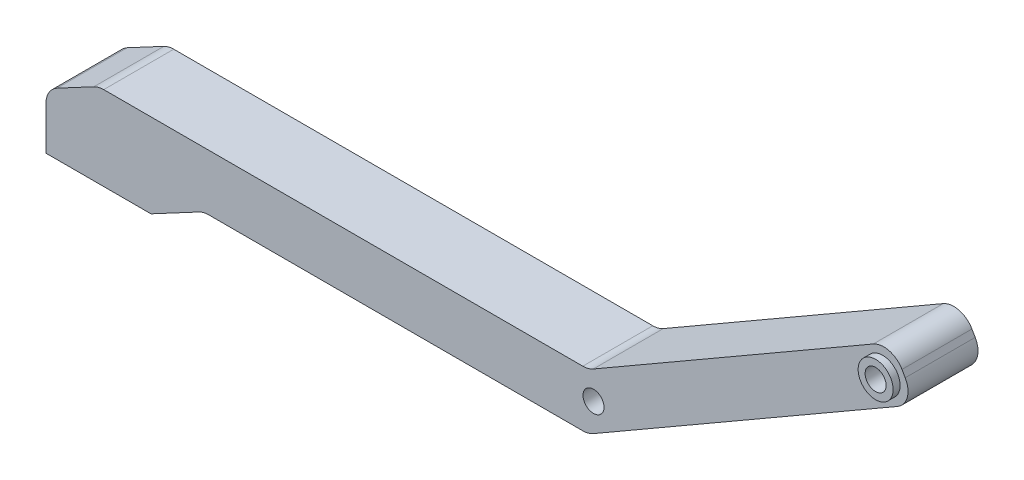
SolidWorks part; units mm, degrees
ref_plane "前视基准面" through (0, 0, 0) normal (0, 0, 1) x (1, 0, 0)
ref_plane "上视基准面" through (0, 0, 0) normal (0, 1, 0) x (1, 0, 0)
ref_plane "右视基准面" through (0, 0, 0) normal (1, 0, 0) x (0, 0, -1)
sketch "草图1" plane through (0, 0, 0) normal (0, 0, 1) x (1, 0, 0)
  line L2 (-7.5, 4) -> (-7.5, -4)
  line L3 (-7.5, -4) -> (7.5, -4)
  line L5 (-7.5, 4) -> (7.5, -4) construction
  line L6 (-7.5, -4) -> (7.5, 4) construction
  line L8 (0, 8) -> (70, 8)
  line L10 (0, 8) -> (-7.5, 4)
  line L11 (7.5, -4) -> (15, 0)
  line L12 (70, 0) -> (116.7654, 27)
  line L13 (116.7654, 27) -> (113.3013, 33)
  line L14 (70, 8) -> (113.3013, 33)
  line L15 (15, 0) -> (70, 0)
  circle A0 centre (112.0369, 28.27) radius 1.5
  circle A1 centre (70.7275, 4.42) radius 1.5
  point P0 (0, 0)
extrude "凸台-拉伸1" add sketch "草图1" along normal blind 10
fillet "圆角1" radius 3 7 edges at (15, 0, 5) (113.3013, 33, 5) (116.7654, 27, 5) (70, 0, 5) (70, 8, 5) (0, 8, 5) (-7.5, 4, 5)
sketch "草图2" plane through (0, 0, 10) normal (0, 0, 1) x (1, 0, 0)
  circle A1 centre (112.0369, 28.27) radius 2.5
  circle A3 centre (112.0369, 28.27) radius 1.5
extrude "凸台-拉伸2" add sketch "草图2" along normal blind 1
